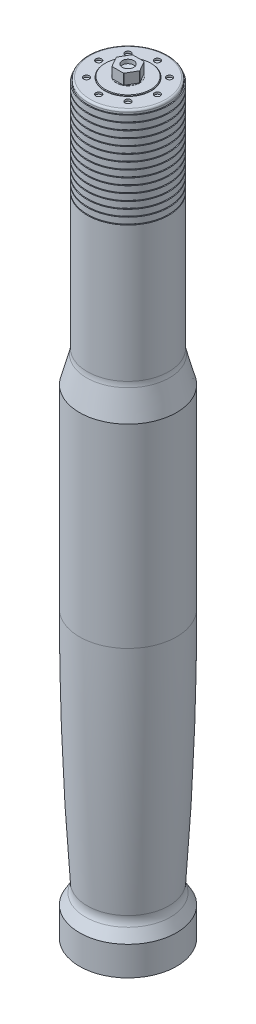
SolidWorks part; units mm, degrees
other "Markup1"
sketch "Sketch11" plane through (-27.903, 202, -26.6723) normal (-0.4071, 0.3981, -0.8221) x (-0.8853, 0.0493, 0.4623)
material "6061 Alloy"
ref_plane "Front Plane" through (0, 0, 0) normal (0, 0, 1) x (1, 0, 0)
ref_plane "Top Plane" through (0, 0, 0) normal (0, 1, 0) x (1, 0, 0)
ref_plane "Right Plane" through (0, 0, 0) normal (1, 0, 0) x (0, 0, -1)
sketch "Sketch1" plane through (0, 0, 0) normal (0, 0, 1) x (1, 0, 0)
  line L0 (0, 0) -> (0, 33.9985) construction
  line L1 (-19, 190.9248) -> (-19, -190.9248)
  line L2 (-19, 190.9248) -> (-21, 190.9248)
  line L3 (-21, 190.9248) -> (-21, 187.9248)
  line L4 (-21.3407, 69.6531) -> (-25, 55.9966)
  line L5 (-25, 55.9966) -> (-25, -44.0034)
  line L6 (-25, -175.9248) -> (-21.8817, -170.5238)
  line L7 (-25, -175.9248) -> (-25, -190.9248)
  line L8 (-25, -190.9248) -> (-19, -190.9248)
  line L9 (-21, 184.4248) -> (-20.5, 184.4248)
  line L10 (-21, 187.9248) -> (-20.5, 187.9248)
  line L11 (-21, 183.9248) -> (-21, 180.9248)
  line L12 (-21, 187.4248) -> (-20.5, 187.4248)
  line L13 (-20.5, 187.9248) -> (-20.5, 187.4248)
  line L14 (-21, 183.9248) -> (-20.5, 183.9248)
  line L15 (-20.5, 184.4248) -> (-20.5, 183.9248)
  line L16 (-21, 180.9248) -> (-20.5, 180.9248)
  line L17 (-21, 180.4248) -> (-20.5, 180.4248)
  line L18 (-20.5, 180.9248) -> (-20.5, 180.4248)
  line L19 (-21, 177.4248) -> (-20.5, 177.4248)
  line L20 (-21, 176.9248) -> (-20.5, 176.9248)
  line L21 (-20.5, 177.4248) -> (-20.5, 176.9248)
  line L22 (-21, 173.9248) -> (-20.5, 173.9248)
  line L23 (-21, 173.4248) -> (-20.5, 173.4248)
  line L24 (-20.5, 173.9248) -> (-20.5, 173.4248)
  line L25 (-21, 170.4248) -> (-20.5, 170.4248)
  line L26 (-21, 169.9248) -> (-20.5, 169.9248)
  line L27 (-20.5, 170.4248) -> (-20.5, 169.9248)
  line L28 (-21, 166.9248) -> (-20.5, 166.9248)
  line L29 (-21, 166.4248) -> (-20.5, 166.4248)
  line L30 (-20.5, 166.9248) -> (-20.5, 166.4248)
  line L31 (-21, 163.4248) -> (-20.5, 163.4248)
  line L32 (-21, 162.9248) -> (-20.5, 162.9248)
  line L33 (-20.5, 163.4248) -> (-20.5, 162.9248)
  line L34 (-21, 159.9248) -> (-20.5, 159.9248)
  line L35 (-21, 159.4248) -> (-20.5, 159.4248)
  line L36 (-20.5, 159.9248) -> (-20.5, 159.4248)
  line L37 (-21, 156.4248) -> (-20.5, 156.4248)
  line L38 (-21, 155.9248) -> (-20.5, 155.9248)
  line L39 (-20.5, 156.4248) -> (-20.5, 155.9248)
  line L40 (-21, 152.9248) -> (-20.5, 152.9248)
  line L41 (-21, 152.4248) -> (-20.5, 152.4248)
  line L42 (-20.5, 152.9248) -> (-20.5, 152.4248)
  line L43 (-21, 149.4248) -> (-20.5, 149.4248)
  line L44 (-21, 148.9248) -> (-20.5, 148.9248)
  line L45 (-20.5, 149.4248) -> (-20.5, 148.9248)
  line L46 (-21, 145.9248) -> (-20.5, 145.9248)
  line L47 (-21, 145.4248) -> (-20.5, 145.4248)
  line L48 (-20.5, 145.9248) -> (-20.5, 145.4248)
  line L49 (-21, 142.4248) -> (-20.5, 142.4248)
  line L50 (-21, 141.9248) -> (-20.5, 141.9248)
  line L51 (-20.5, 142.4248) -> (-20.5, 141.9248)
  line L52 (-21, 187.4248) -> (-21, 184.4248)
  line L53 (-21, 180.4248) -> (-21, 177.4248)
  line L54 (-21, 176.9248) -> (-21, 173.9248)
  line L55 (-21, 173.4248) -> (-21, 170.4248)
  line L56 (-21, 169.9248) -> (-21, 166.9248)
  line L57 (-21, 166.4248) -> (-21, 163.4248)
  line L58 (-21, 162.9248) -> (-21, 159.9248)
  line L59 (-21, 159.4248) -> (-21, 156.4248)
  line L60 (-21, 155.9248) -> (-21, 152.9248)
  line L61 (-21, 152.4248) -> (-21, 149.4248)
  line L62 (-21, 148.9248) -> (-21, 145.9248)
  line L63 (-21, 141.9248) -> (-21, 72.2413)
  line L64 (-21, 145.4248) -> (-21, 142.4248)
  arc A0 (-25, -44.0034) -> (-21, -165.9248) centre (1835.1014, -44.0034) ccw
  arc A1 (-21, 72.2413) -> (-21.3407, 69.6531) centre (-31, 72.2413) cw
  arc A2 (-21.8817, -170.5238) -> (-21, -165.9248) centre (-28.064, -166.9545) ccw
  point P5 (-19, 0)
  point P16 (-21, 70.9248)
  dimension "D11" = 10
  dimension "D12" = 30
  dimension "D1" = 381.8495
  dimension "D2" = 38
  dimension "D3" = 42
  dimension "D4" = 4
  dimension "D5" = 15
  dimension "D6" = 120
  dimension "D7" = 25
  dimension "D8" = 2
  dimension "D9" = 15
  dimension "D10" = 100
  dimension "D13" = 0.5
  dimension "D14" = 0.5
  dimension "D15" = 3
  dimension "D17" = 3
  dimension "D16" = 14
revolve "Revolve1" add sketch "Sketch1" angle 360 about L0
sketch "Sketch4" plane through (0, 0, 0) normal (1, 0, 0) x (0, 0, -1)
  line L1 (-20.5, 190.9248) -> (0, 190.9248)
  line L2 (-20.5, 190.9248) -> (-20.5, 191.9248)
  line L3 (-19.5, 192.9248) -> (0, 192.9248)
  line L5 (21, 190.9248) -> (-21, 190.9248) construction
  line L10 (0, 192.9248) -> (0, 190.9248)
  arc A1 (-20.5, 191.9248) -> (-19.5, 192.9248) centre (-19.5, 191.9248) cw
  point P14 (-20.5, 192.9248)
  dimension "D3" = 1
  dimension "D1" = 2
  dimension "D2" = 20.5
revolve "Revolve2" add sketch "Sketch4" angle 360 about L10
sketch "Sketch6" plane through (0, 0, 0) normal (1, 0, 0) x (0, 0, -1)
  line L0 (0, 192.9248) -> (0, 198.9248)
  line L1 (19.5, 192.9248) -> (-19.5, 192.9248) construction
  line L2 (0, 198.9248) -> (-6, 198.9248)
  line L3 (-6, 198.9248) -> (-6, 193.4248)
  line L4 (-6, 193.4248) -> (-11.7, 193.4248)
  line L5 (-12, 193.1248) -> (-12, 192.9248)
  line L6 (-12, 192.9248) -> (0, 192.9248)
  line L7 (-12, 193.1248) -> (-11.7, 193.4248)
  dimension "D1" = 6
  dimension "D2" = 6
  dimension "D3" = 12
  dimension "D4" = 0.5
  dimension "D5" = 45
  dimension "D6" = 0.2
revolve "Revolve4" add sketch "Sketch6" angle 360 about L0
sketch "Sketch7" plane through (0, 198.9248, 0) normal (0, 1, 0) x (1, 0, 0)
  line L1 (5.999, 0.1094) -> (3.0943, 5.1406)
  line L2 (2.9047, 5.25) -> (-2.9047, 5.25)
  line L3 (-3.0943, 5.1406) -> (-5.999, 0.1094)
  line L4 (-5.999, -0.1094) -> (-3.0943, -5.1406)
  line L5 (-2.9047, -5.25) -> (2.9047, -5.25)
  line L6 (3.0943, -5.1406) -> (5.999, -0.1094)
  circle A0 centre (0, 0) radius 5.25 construction
  arc A1 (-3.0943, 5.1406) -> (-5.999, 0.1094) centre (0, 0) ccw
  circle A2 centre (0, 0) radius 6 construction
  arc A3 (2.9047, 5.25) -> (-2.9047, 5.25) centre (0, 0) ccw
  arc A4 (5.999, 0.1094) -> (3.0943, 5.1406) centre (0, 0) ccw
  arc A5 (3.0943, -5.1406) -> (5.999, -0.1094) centre (0, 0) ccw
  arc A6 (-2.9047, -5.25) -> (2.9047, -5.25) centre (0, 0) ccw
  arc A7 (-5.999, -0.1094) -> (-3.0943, -5.1406) centre (0, 0) ccw
  circle A8 centre (0, 0) radius 1
  point P16 (0, -5.25)
  dimension "D1" = 10.5
  dimension "D2" = 2
extrude "Cut-Extrude1" cut sketch "Sketch7" against normal offset from surface (5.4 mm away) 0.1 up to face at (0, 193.4248, -11.7)
sketch "Sketch9" plane through (0, 0, 0) normal (1, 0, 0) x (0, 0, -1)
  line L0 (0, 198.9248) -> (0, 195.9248)
  line L2 (0, 195.9248) -> (-3, 196.9248)
  line L3 (-3, 196.9248) -> (-3, 198.9248)
  line L4 (-0.1094, 198.9248) -> (-5.1406, 198.9248) construction
  line L5 (-3, 198.9248) -> (0, 198.9248)
  dimension "D1" = 3
  dimension "D2" = 2
  dimension "D3" = 3
revolve "Cut-Revolve1" cut sketch "Sketch9" angle 360 about L0
sketch "Sketch10" plane through (0, 0, 0) normal (1, 0, 0) x (0, 0, -1)
  line L0 (-15.1, 192.9248) -> (-15.1, 191.0587)
  line L1 (19.5, 192.9248) -> (-19.5, 192.9248) construction
  line L2 (-15.1, 191.0587) -> (-16.6, 191.9248)
  line L3 (-16.6, 191.9248) -> (-16.6, 192.9248)
  line L4 (-16.6, 192.9248) -> (-15.1, 192.9248)
  dimension "D1" = 1.5
  dimension "D2" = 3.1
  dimension "D3" = 60
  dimension "D4" = 1
revolve "Cut-Revolve2" cut sketch "Sketch10" angle 360 about L0
pattern_circular "CirPattern2" count 8 over 360 about axis through (0, 0, 0) along (0, 1, 0) of "Cut-Revolve2"
